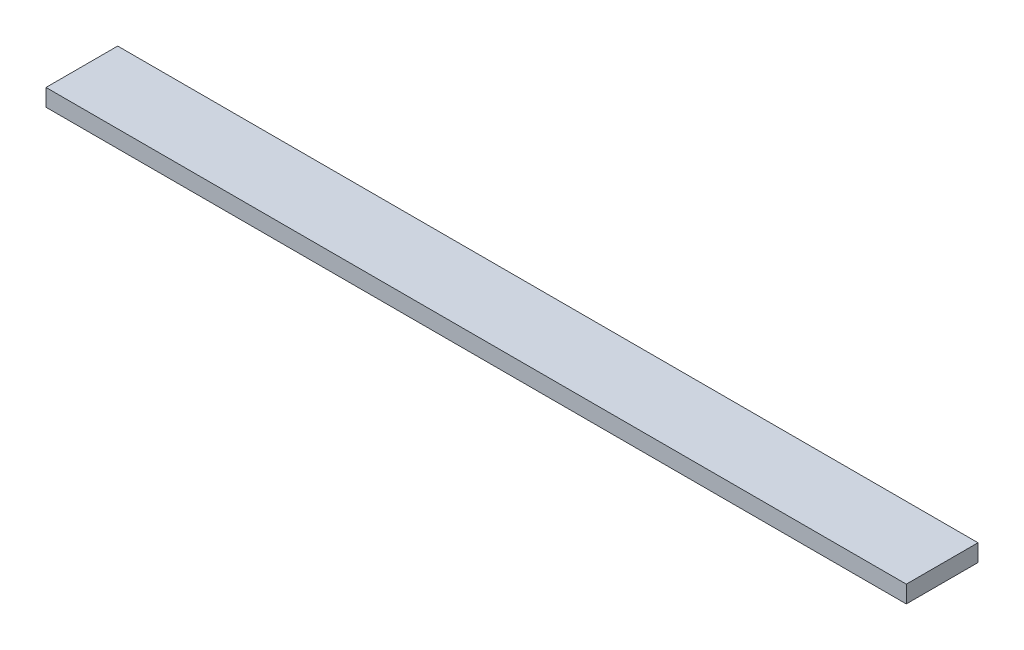
SolidWorks part; units mm, degrees
ref_plane "Front Plane" through (0, 0, 0) normal (0, 0, 1) x (1, 0, 0)
ref_plane "Top Plane" through (0, 0, 0) normal (0, 1, 0) x (1, 0, 0)
ref_plane "Right Plane" through (0, 0, 0) normal (1, 0, 0) x (0, 0, -1)
sketch "Sketch1" plane through (0, 0, 0) normal (0, 1, 0) x (1, 0, 0)
  line L1 (-457.2, -38.1) -> (457.2, -38.1)
  line L2 (-457.2, -38.1) -> (-457.2, 38.1)
  line L3 (-457.2, 38.1) -> (457.2, 38.1)
  line L4 (457.2, -38.1) -> (457.2, 38.1)
  line L5 (-457.2, -38.1) -> (457.2, 38.1) construction
  line L6 (-457.2, 38.1) -> (457.2, -38.1) construction
  point P0 (0, 0)
  dimension "D1" = 914.4
  dimension "D2" = 76.2
extrude "Boss-Extrude1" add sketch "Sketch1" along normal blind 18.2562
